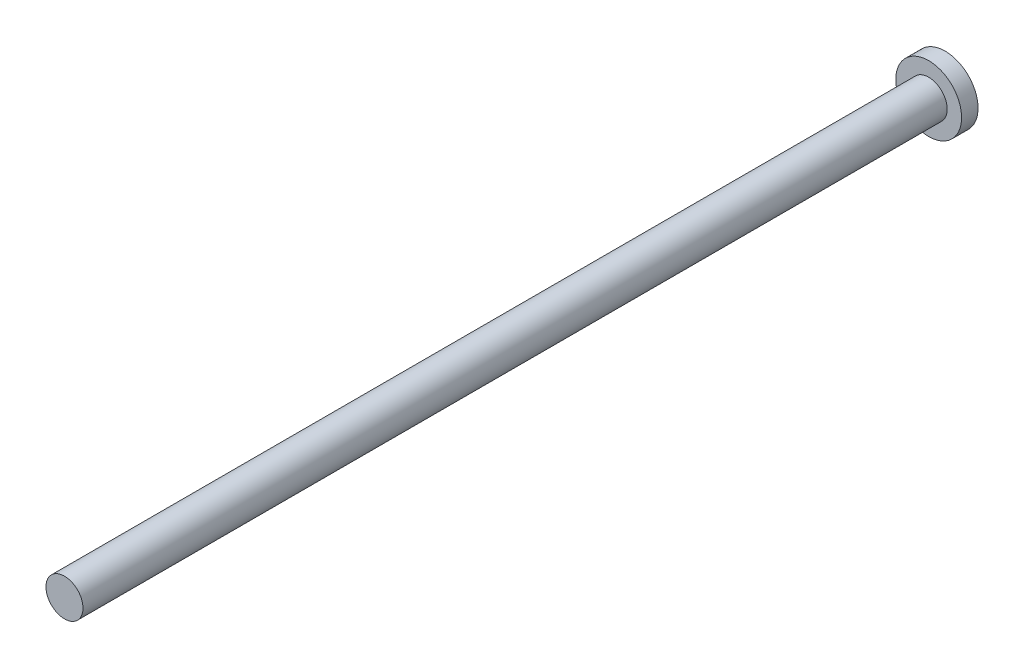
SolidWorks part; units mm, degrees
ref_plane "Front Plane" through (0, 0, 0) normal (0, 0, 1) x (1, 0, 0)
ref_plane "Top Plane" through (0, 0, 0) normal (0, 1, 0) x (1, 0, 0)
ref_plane "Right Plane" through (0, 0, 0) normal (1, 0, 0) x (0, 0, -1)
sketch "Sketch1" plane through (0, 0, 0) normal (0, 0, 1) x (1, 0, 0)
  circle A0 centre (0, 0) radius 2.8575
  dimension "D1" = 5.715
extrude "Boss-Extrude1" add sketch "Sketch1" along normal blind 133.35
sketch "Sketch2" plane through (0, 0, 0) normal (0, 0, -1) x (-1, 0, 0)
  circle A0 centre (0, 0) radius 5.08
  dimension "D1" = 10.16
extrude "Boss-Extrude2" add sketch "Sketch2" along normal blind 2.54 contours A0
